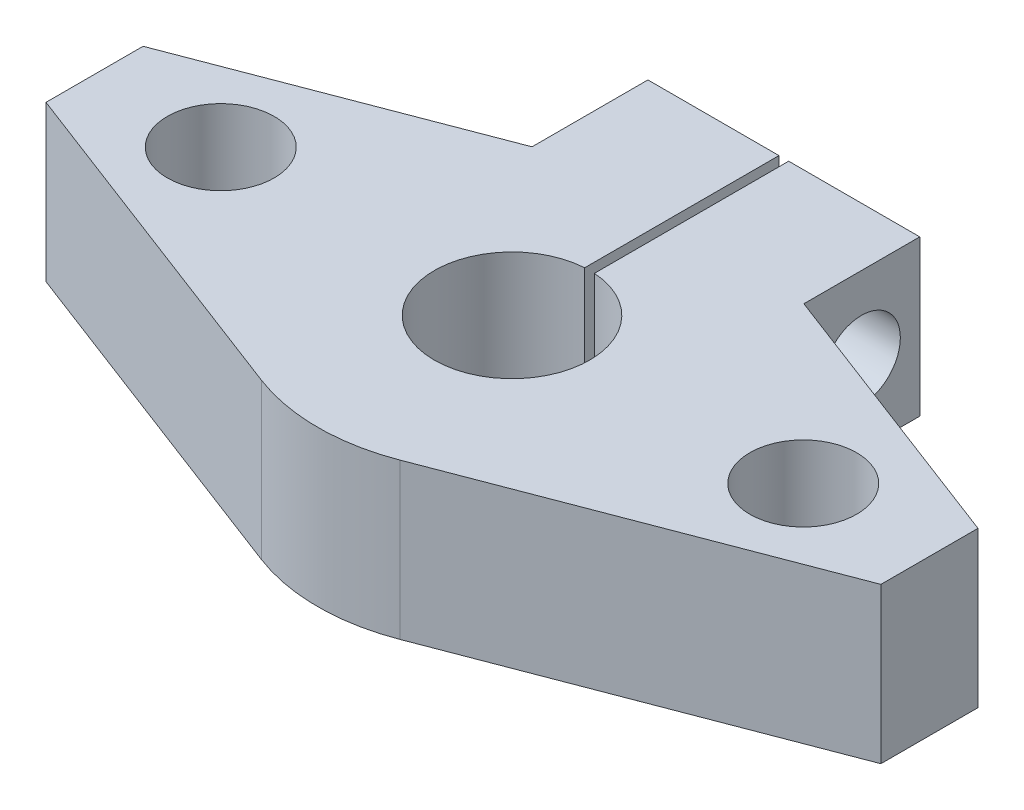
SolidWorks part; units mm, degrees
other "Kamera1"
ref_plane "Front Plane" through (0, 0, 0) normal (0, 0, 1) x (1, 0, 0)
ref_plane "Top Plane" through (0, 0, 0) normal (0, 1, 0) x (1, 0, 0)
ref_plane "Right Plane" through (0, 0, 0) normal (1, 0, 0) x (0, 0, -1)
sketch "Sketch1" plane through (0, 0, 0) normal (0, 1, 0) x (1, 0, 0)
  line L0 (0, 14) -> (0, -10)
  line L1 (-21.5, 2.5) -> (-21.5, -2.5)
  line L3 (-21.5, 0) -> (27.7491, 0) construction
  line L6 (-21.5, 2.5) -> (-7, 8.0324)
  line L7 (-21.5, -2.5) -> (-3.5648, -9.343)
  line L17 (0, 14) -> (-7, 14)
  line L19 (-7, 14) -> (-7, 8.0324)
  arc A1 (-3.5648, -9.343) -> (0, -10) centre (0, 0) ccw
  circle A2 centre (-15, 0) radius 2.75
  point P1 (0, 0)
  point P3 (0, 0)
  point P4 (-15, 0)
  point P5 (-21.5, 9.8473)
  point P6 (-21.5, -13.603)
  point P7 (21.5, 9.8473)
  point P8 (21.5, -13.603)
  point P12 (-22.507, 2.9498)
  point P13 (-7.4151, 7.9273)
  point P14 (-0.4668, 5.4915)
  point P15 (0, 12.2479)
  dimension "D4" = 24
  dimension "D7" = 5.5
  dimension "D6" = 5
  dimension "D3" = 10
  dimension "D11" = 7
  dimension "D2" = 15
  dimension "D5" = 21.5
extrude "Boss-Extrude1" add sketch "Sketch1" along normal blind 8
mirror "Simetría1" about plane through (0, 8, -14) normal (-1, 0, 0) of "Boss-Extrude1"
sketch "Sketch2" plane through (0, 8, 0) normal (0, 1, 0) x (1, 0, 0)
  circle A0 centre (0, 0) radius 10
extrude "Saliente-Extruir1" [suppressed] add sketch "Sketch2" along normal blind 5
sketch "Croquis1" plane through (0, 0, 0) normal (0, 1, 0) x (1, 0, 0)
  circle A0 centre (0, 0) radius 4
  dimension "D1" = 8
extrude "Cortar-Extruir1" cut sketch "Croquis1" along normal through all
sketch "Croquis2" plane through (0, 0, 0) normal (0, 1, 0) x (1, 0, 0)
  line L1 (-0.25, 20) -> (0.25, 20)
  line L2 (-0.25, 20) -> (-0.25, 0)
  line L3 (-0.25, 0) -> (0.25, 0)
  line L4 (0.25, 20) -> (0.25, 0)
  line L5 (-0.25, 20) -> (0.25, 0) construction
  line L6 (-0.25, 0) -> (0.25, 20) construction
  point P0 (0, 10)
  point P7 (0, 0)
  point P8 (0, 0)
  point P10 (2.368, 0.0209)
  point P11 (0, 0)
  dimension "D1" = 0.5
extrude "Cortar-Extruir2" cut sketch "Croquis2" along normal through all
sketch "Sketch3" plane through (7, 0, 0) normal (1, 0, 0) x (0, 0, -1)
  line L0 (14, 0) -> (8.0324, 0) construction
  line L1 (14, 8) -> (14, 0) construction
  circle A0 centre (11, 4) radius 2
  dimension "D1" = 4
  dimension "D2" = 4
  dimension "D3" = 3
extrude "Cut-Extrude1" cut sketch "Sketch3" against normal through all
